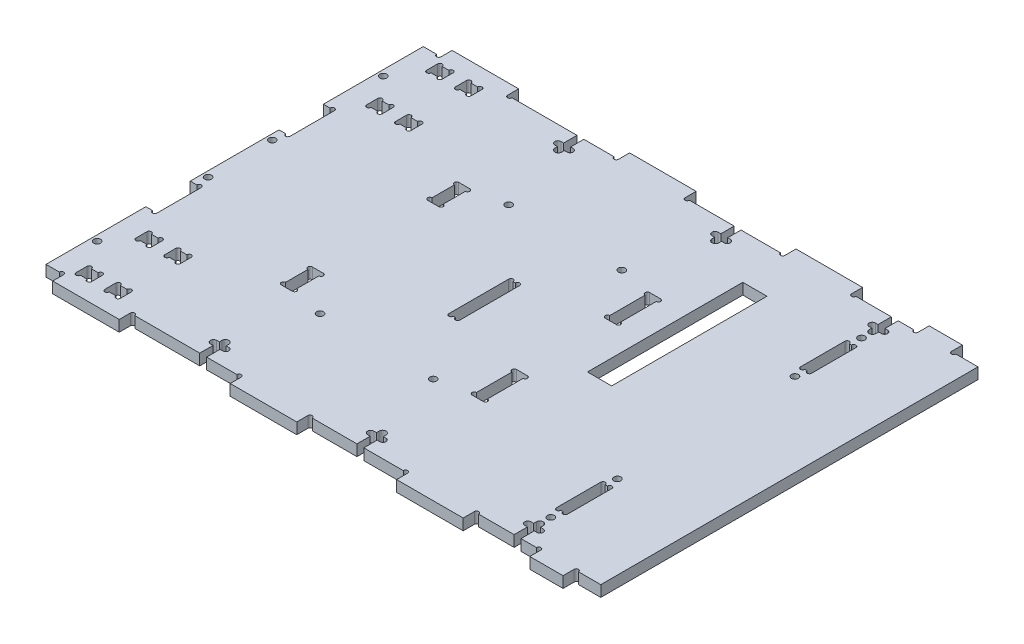
SolidWorks part; units mm, degrees
ref_plane "정면" through (0, 0, 0) normal (0, 0, 1) x (1, 0, 0)
ref_plane "윗면" through (0, 0, 0) normal (0, 1, 0) x (1, 0, 0)
ref_plane "우측면" through (0, 0, 0) normal (1, 0, 0) x (0, 0, -1)
sketch "스케치1" plane through (0, 0, 0) normal (0, 1, 0) x (1, 0, 0)
  line L1 (0, 0) -> (250, 0)
  line L2 (0, 0) -> (0, 170)
  line L3 (0, 170) -> (250, 170)
  line L4 (250, 0) -> (250, 170)
  dimension "D1" = 170
  dimension "D2" = 250
extrude "보스-돌출1" add sketch "스케치1" along normal blind 5
sketch "스케치2" plane through (0, 0, 0) normal (0, -1, 0) x (1, 0, 0)
  line L0 (110, -71.5) -> (110, 0) construction
  line L1 (110, -71.5) -> (115, -71.5)
  line L2 (110, -71.5) -> (110, -98.5)
  line L3 (110, -98.5) -> (115, -98.5)
  line L4 (115, -71.5) -> (115, -98.5)
  line L5 (0, 0) -> (250, 0) construction
  line L6 (110, -98.5) -> (110, -170) construction
  line L7 (250, -170) -> (0, -170) construction
  line L10 (250, 0) -> (250, -170) construction
  line L11 (210, 0) -> (210, -20) construction
  line L12 (210, -20) -> (215, -20)
  line L13 (210, -20) -> (210, -40)
  line L14 (210, -40) -> (215, -40)
  line L15 (215, -20) -> (215, -40)
  line L16 (210, -130) -> (215, -130)
  line L17 (210, -130) -> (210, -150)
  line L18 (210, -150) -> (215, -150)
  line L19 (215, -130) -> (215, -150)
  line L20 (210, -40) -> (210, -130) construction
  line L21 (210, -150) -> (210, -170) construction
  line L22 (215, -130) -> (215, -40) construction
  dimension "D1" = 27
  dimension "D2" = 140
  dimension "D3" = 5
  dimension "D4" = 20
  dimension "D5" = 20
  dimension "D6" = 40
  dimension "D7" = 5
extrude "컷-돌출1" cut sketch "스케치2" against normal blind 10
sketch "스케치3" plane through (0, 5, 0) normal (0, 1, 0) x (1, 0, 0)
  line L0 (133.55, 42.5) -> (130.45, 42.5) construction
  line L1 (133.55, 40) -> (133.55, 45) construction
  line L2 (130.45, 40) -> (130.45, 45) construction
  line L3 (130.45, 42.5) -> (82.55, 42.5) construction
  line L4 (82.55, 40) -> (82.55, 45) construction
  line L5 (82.55, 42.5) -> (79.45, 42.5) construction
  line L6 (79.45, 40) -> (79.45, 45) construction
  line L7 (133.55, 127.5) -> (130.45, 127.5) construction
  line L8 (133.55, 125) -> (133.55, 130) construction
  line L9 (130.45, 125) -> (130.45, 130) construction
  line L10 (130.45, 127.5) -> (82.55, 127.5) construction
  line L11 (82.55, 125) -> (82.55, 130) construction
  line L12 (82.55, 127.5) -> (79.45, 127.5) construction
  line L13 (79.45, 125) -> (79.45, 130) construction
  line L14 (212.5, 46.55) -> (212.5, 43.45) construction
  line L15 (2.5, 101) -> (2.5, 97.9) construction
  line L16 (215, 46.55) -> (210, 46.55) construction
  line L17 (5, 101) -> (0, 101) construction
  line L18 (212.5, 16.55) -> (212.5, 13.45) construction
  line L19 (215, 16.55) -> (210, 16.55) construction
  line L20 (215, 13.45) -> (210, 13.45) construction
  line L21 (215, 43.45) -> (210, 43.45) construction
  line L22 (212.5, 126.55) -> (212.5, 123.45) construction
  line L23 (215, 126.55) -> (210, 126.55) construction
  line L24 (215, 123.45) -> (210, 123.45) construction
  line L25 (212.5, 156.55) -> (212.5, 153.45) construction
  line L26 (215, 156.55) -> (210, 156.55) construction
  line L27 (215, 153.45) -> (210, 153.45) construction
  line L28 (5, 97.9) -> (0, 97.9) construction
  line L31 (2.5, 151) -> (2.5, 147.9) construction
  line L34 (2.5, 22.1) -> (2.5, 19) construction
  line L35 (5, 22.1) -> (0, 22.1) construction
  line L36 (5, 19) -> (0, 19) construction
  line L37 (2.5, 72.1) -> (2.5, 69) construction
  line L38 (5, 72.1) -> (0, 72.1) construction
  line L39 (5, 69) -> (0, 69) construction
  line L40 (5, 151) -> (0, 151) construction
  line L41 (5, 147.9) -> (0, 147.9) construction
  circle A0 centre (81, 127.5) radius 1.55
  circle A1 centre (132, 127.5) radius 1.55
  circle A2 centre (132, 42.5) radius 1.55
  circle A3 centre (81, 42.5) radius 1.55
  circle A4 centre (2.5, 70.55) radius 1.55
  circle A5 centre (2.5, 20.55) radius 1.55
  circle A6 centre (2.5, 99.45) radius 1.55
  circle A7 centre (2.5, 149.45) radius 1.55
  circle A8 centre (212.5, 155) radius 1.55
  circle A9 centre (212.5, 125) radius 1.55
  circle A10 centre (212.5, 15) radius 1.55
  circle A11 centre (212.5, 45) radius 1.55
  dimension "D1" = 3.1
extrude "컷-돌출2" cut sketch "스케치3" against normal blind 10
sketch "스케치4" plane through (0, 0, 0) normal (0, -1, 0) x (1, 0, 0)
  line L1 (0, -125) -> (5, -125)
  line L2 (0, -125) -> (0, -105)
  line L3 (0, -105) -> (5, -105)
  line L4 (5, -125) -> (5, -105)
  line L5 (0, -65) -> (5, -65)
  line L6 (0, -65) -> (0, -45)
  line L7 (0, -45) -> (5, -45)
  line L8 (5, -65) -> (5, -45)
extrude "컷-돌출3" cut sketch "스케치4" against normal blind 5
sketch "스케치5" plane through (0, 0, 0) normal (0, -1, 0) x (1, 0, 0)
  line L2 (5, -45) -> (0, -45) construction
  line L3 (0, -65) -> (5, -65) construction
  line L4 (5, -105) -> (0, -105) construction
  line L5 (0, -125) -> (5, -125) construction
  line L6 (110, -98.5) -> (115, -98.5) construction
  line L7 (115, -71.5) -> (110, -71.5) construction
  line L8 (215, -20) -> (210, -20) construction
  line L9 (210, -40) -> (215, -40) construction
  line L10 (215, -130) -> (210, -130) construction
  line L11 (210, -150) -> (215, -150) construction
  circle A1 centre (4, -45) radius 1
  circle A2 centre (4, -65) radius 1
  circle A5 centre (4, -105) radius 1
  circle A6 centre (4, -125) radius 1
  circle A8 centre (114, -98.5) radius 1
  circle A9 centre (111, -98.5) radius 1
  circle A10 centre (114, -71.5) radius 1
  circle A11 centre (111, -71.5) radius 1
  circle A12 centre (214, -20) radius 1
  circle A13 centre (211, -20) radius 1
  circle A14 centre (214, -40) radius 1
  circle A15 centre (211, -40) radius 1
  circle A16 centre (214, -130) radius 1
  circle A17 centre (211, -130) radius 1
  circle A18 centre (214, -150) radius 1
  circle A19 centre (211, -150) radius 1
  dimension "D1" = 2
extrude "컷-돌출4" cut sketch "스케치5" against normal blind 10
sketch "스케치7" plane through (0, 0, 0) normal (0, -1, 0) x (1, 0, 0)
  line L0 (70.8333, -157.529) -> (0, -157.529) construction
  line L1 (215.25, -8.8) -> (214.05, -8.8)
  line L2 (214.05, 0) -> (214.05, -6)
  line L3 (214.05, -6) -> (210.95, -6) construction
  line L4 (215.25, -6) -> (215.25, -8.8) construction
  line L5 (209.75, -8.8) -> (209.75, -6) construction
  line L6 (212.5, -10) -> (212.5, -12.471) construction
  line L7 (214.05, -10) -> (210.95, -10) construction
  line L8 (209.75, -6) -> (210.95, -6)
  line L9 (210.95, -6) -> (210.95, -8.8) construction
  line L10 (210.95, 0) -> (210.95, -6)
  line L11 (210.95, -8.8) -> (209.75, -8.8)
  line L12 (214.05, -8.8) -> (214.05, -6) construction
  line L13 (210.95, -8.8) -> (210.95, -10)
  line L14 (214.05, -8.8) -> (210.95, -8.8) construction
  line L15 (214.05, -8.8) -> (214.05, -10)
  line L16 (214.05, -6) -> (215.25, -6)
  line L17 (214.05, 0) -> (210.95, 0)
  line L18 (0, -45) -> (0, 0) construction
  line L19 (141.6667, -157.529) -> (70.8333, -157.529) construction
  line L20 (141.6667, -157.529) -> (212.5, -157.529) construction
  line L21 (212.5, -150) -> (212.5, -153.45) construction
  line L22 (143.2167, -161.2) -> (140.1167, -161.2) construction
  line L23 (143.2167, -161.2) -> (143.2167, -164) construction
  line L24 (140.1167, -164) -> (140.1167, -161.2) construction
  line L25 (143.2167, -160) -> (140.1167, -160) construction
  line L26 (141.6667, -160) -> (141.6667, -157.529) construction
  line L27 (138.9167, -161.2) -> (138.9167, -164) construction
  line L28 (144.4167, -164) -> (144.4167, -161.2) construction
  line L29 (143.2167, -164) -> (140.1167, -164) construction
  line L30 (72.3833, -161.2) -> (69.2833, -161.2) construction
  line L31 (72.3833, -161.2) -> (72.3833, -164) construction
  line L32 (69.2833, -164) -> (69.2833, -161.2) construction
  line L33 (72.3833, -160) -> (69.2833, -160) construction
  line L34 (70.8333, -160) -> (70.8333, -157.529) construction
  line L35 (73.5833, -8.8) -> (72.3833, -8.8)
  line L36 (72.3833, 0) -> (72.3833, -6)
  line L37 (72.3833, -6) -> (69.2833, -6) construction
  line L38 (73.5833, -6) -> (73.5833, -8.8) construction
  line L39 (68.0833, -8.8) -> (68.0833, -6) construction
  line L40 (70.8333, -10) -> (70.8333, -12.471) construction
  line L41 (72.3833, -10) -> (69.2833, -10) construction
  line L42 (68.0833, -6) -> (69.2833, -6)
  line L43 (69.2833, -6) -> (69.2833, -8.8) construction
  line L44 (69.2833, 0) -> (69.2833, -6)
  line L45 (69.2833, -8.8) -> (68.0833, -8.8)
  line L46 (72.3833, -8.8) -> (72.3833, -6) construction
  line L47 (69.2833, -8.8) -> (69.2833, -10)
  line L48 (72.3833, -8.8) -> (69.2833, -8.8) construction
  line L49 (72.3833, -8.8) -> (72.3833, -10)
  line L50 (72.3833, -6) -> (73.5833, -6)
  line L51 (72.3833, 0) -> (69.2833, 0)
  line L52 (144.4167, -8.8) -> (143.2167, -8.8)
  line L53 (143.2167, 0) -> (143.2167, -6)
  line L54 (143.2167, -6) -> (140.1167, -6) construction
  line L55 (144.4167, -6) -> (144.4167, -8.8) construction
  line L56 (138.9167, -8.8) -> (138.9167, -6) construction
  line L57 (141.6667, -10) -> (141.6667, -12.471) construction
  line L58 (143.2167, -10) -> (140.1167, -10) construction
  line L59 (138.9167, -6) -> (140.1167, -6)
  line L60 (140.1167, -6) -> (140.1167, -8.8) construction
  line L61 (140.1167, 0) -> (140.1167, -6)
  line L62 (140.1167, -8.8) -> (138.9167, -8.8)
  line L63 (143.2167, -8.8) -> (143.2167, -6) construction
  line L64 (140.1167, -8.8) -> (140.1167, -10)
  line L65 (143.2167, -8.8) -> (140.1167, -8.8) construction
  line L66 (143.2167, -8.8) -> (143.2167, -10)
  line L67 (143.2167, -6) -> (144.4167, -6)
  line L68 (143.2167, 0) -> (140.1167, 0)
  line L69 (68.0833, -161.2) -> (68.0833, -164) construction
  line L70 (212.5, -20) -> (212.5, -16.55) construction
  line L71 (213, -20) -> (212, -20) construction
  line L72 (141.6667, -12.471) -> (212.5, -12.471) construction
  line L73 (141.6667, -12.471) -> (70.8333, -12.471) construction
  line L74 (70.8333, -12.471) -> (0, -12.471) construction
  line L75 (0, -85) -> (250, -85) construction
  line L76 (0, -105) -> (0, -65) construction
  line L77 (250, 0) -> (250, -170) construction
  line L78 (73.5833, -164) -> (73.5833, -161.2) construction
  line L79 (72.3833, -164) -> (69.2833, -164) construction
  line L80 (214.05, -161.2) -> (210.95, -161.2) construction
  line L81 (214.05, -161.2) -> (214.05, -164) construction
  line L82 (210.95, -164) -> (210.95, -161.2) construction
  line L83 (214.05, -160) -> (210.95, -160) construction
  line L84 (212.5, -160) -> (212.5, -157.529) construction
  line L85 (209.75, -161.2) -> (209.75, -164) construction
  line L86 (215.25, -164) -> (215.25, -161.2) construction
  line L87 (214.05, -164) -> (210.95, -164) construction
  line L88 (143.2167, -170) -> (140.1167, -170)
  line L89 (143.2167, -164) -> (144.4167, -164)
  line L90 (143.2167, -161.2) -> (143.2167, -160)
  line L91 (140.1167, -161.2) -> (140.1167, -160)
  line L92 (140.1167, -161.2) -> (138.9167, -161.2)
  line L93 (140.1167, -170) -> (140.1167, -164)
  line L94 (138.9167, -164) -> (140.1167, -164)
  line L95 (143.2167, -170) -> (143.2167, -164)
  line L96 (144.4167, -161.2) -> (143.2167, -161.2)
  line L97 (72.3833, -170) -> (69.2833, -170)
  line L98 (72.3833, -164) -> (73.5833, -164)
  line L99 (72.3833, -161.2) -> (72.3833, -160)
  line L100 (69.2833, -161.2) -> (69.2833, -160)
  line L101 (69.2833, -161.2) -> (68.0833, -161.2)
  line L102 (69.2833, -170) -> (69.2833, -164)
  line L103 (68.0833, -164) -> (69.2833, -164)
  line L104 (72.3833, -170) -> (72.3833, -164)
  line L105 (73.5833, -161.2) -> (72.3833, -161.2)
  line L106 (214.05, -170) -> (210.95, -170)
  line L107 (214.05, -164) -> (215.25, -164)
  line L108 (214.05, -161.2) -> (214.05, -160)
  line L109 (210.95, -161.2) -> (210.95, -160)
  line L110 (210.95, -161.2) -> (209.75, -161.2)
  line L111 (210.95, -170) -> (210.95, -164)
  line L112 (209.75, -164) -> (210.95, -164)
  line L113 (214.05, -170) -> (214.05, -164)
  line L114 (215.25, -161.2) -> (214.05, -161.2)
  arc A0 (209.75, -6) -> (209.75, -8.8) centre (209.75, -7.4) ccw
  arc A1 (215.25, -8.8) -> (215.25, -6) centre (215.25, -7.4) ccw
  arc A2 (210.95, -10) -> (214.05, -10) centre (212.5, -10) ccw
  arc A3 (140.1167, -160) -> (143.2167, -160) centre (141.6667, -160) cw
  arc A4 (144.4167, -161.2) -> (144.4167, -164) centre (144.4167, -162.6) cw
  arc A5 (138.9167, -164) -> (138.9167, -161.2) centre (138.9167, -162.6) cw
  arc A6 (68.0833, -6) -> (68.0833, -8.8) centre (68.0833, -7.4) ccw
  arc A7 (73.5833, -8.8) -> (73.5833, -6) centre (73.5833, -7.4) ccw
  arc A8 (69.2833, -10) -> (72.3833, -10) centre (70.8333, -10) ccw
  arc A9 (138.9167, -6) -> (138.9167, -8.8) centre (138.9167, -7.4) ccw
  arc A10 (144.4167, -8.8) -> (144.4167, -6) centre (144.4167, -7.4) ccw
  arc A11 (140.1167, -10) -> (143.2167, -10) centre (141.6667, -10) ccw
  circle A12 centre (212.5, -15) radius 1.55 construction
  arc A13 (69.2833, -160) -> (72.3833, -160) centre (70.8333, -160) cw
  arc A14 (73.5833, -161.2) -> (73.5833, -164) centre (73.5833, -162.6) cw
  arc A15 (68.0833, -164) -> (68.0833, -161.2) centre (68.0833, -162.6) cw
  arc A16 (210.95, -160) -> (214.05, -160) centre (212.5, -160) cw
  arc A17 (215.25, -161.2) -> (215.25, -164) centre (215.25, -162.6) cw
  arc A18 (209.75, -164) -> (209.75, -161.2) centre (209.75, -162.6) cw
  dimension "D2" = 3.1
  dimension "D3" = 5.5
  dimension "D4" = 2.8
  dimension "D8" = 3.1
  dimension "D9" = 5.5
  dimension "D10" = 2.8
  dimension "D11" = 3.1
  dimension "D12" = 5.5
  dimension "D13" = 2.8
extrude "컷-돌출5" cut sketch "스케치7" against normal blind 10
sketch "스케치8" plane through (0, 0, 0) normal (0, -1, 0) x (1, 0, 0)
  line L0 (0, 0) -> (69.2833, 0) construction
  line L1 (8, 0) -> (38, 0)
  line L2 (8, 0) -> (8, 5)
  line L3 (8, 5) -> (38, 5)
  line L4 (38, 0) -> (38, 5)
  line L5 (0, 5) -> (8, 5) construction
  line L6 (72.3833, 0) -> (140.1167, 0) construction
  line L7 (88, 5) -> (118, 5)
  line L8 (88, 5) -> (88, 0)
  line L9 (88, 0) -> (118, 0)
  line L10 (118, 5) -> (118, 0)
  line L11 (143.2167, 0) -> (210.95, 0) construction
  line L12 (163, 5) -> (193, 5)
  line L13 (163, 5) -> (163, 0)
  line L14 (163, 0) -> (193, 0)
  line L15 (193, 5) -> (193, 0)
  line L16 (214.05, 0) -> (250, 0) construction
  line L17 (223, 5) -> (238, 5)
  line L18 (223, 5) -> (223, 0)
  line L19 (223, 0) -> (238, 0)
  line L20 (238, 5) -> (238, 0)
  line L21 (250, 0) -> (250, -170) construction
  line L22 (0, -85) -> (250, -85) construction
  line L23 (0, -105) -> (0, -65) construction
  line L24 (238, -175) -> (238, -170)
  line L25 (223, -170) -> (238, -170)
  line L26 (223, -175) -> (223, -170)
  line L27 (223, -175) -> (238, -175)
  line L28 (193, -175) -> (193, -170)
  line L29 (163, -170) -> (193, -170)
  line L30 (163, -175) -> (163, -170)
  line L31 (163, -175) -> (193, -175)
  line L32 (118, -175) -> (118, -170)
  line L33 (88, -170) -> (118, -170)
  line L34 (88, -175) -> (88, -170)
  line L35 (88, -175) -> (118, -175)
  line L36 (38, -170) -> (38, -175)
  line L37 (8, -175) -> (38, -175)
  line L38 (8, -170) -> (8, -175)
  line L39 (8, -170) -> (38, -170)
  dimension "D1" = 12
  dimension "D2" = 15
  dimension "D3" = 30
  dimension "D4" = 30
  dimension "D5" = 45
  dimension "D6" = 30
  dimension "D7" = 50
  dimension "D8" = 30
extrude "보스-돌출2" add sketch "스케치8" against normal blind 5
sketch "스케치9" plane through (0, 0, 0) normal (0, -1, 0) x (1, 0, 0)
  line L0 (0, 0) -> (8, 0) construction
  line L1 (38, 0) -> (69.2833, 0) construction
  line L2 (72.3833, 0) -> (88, 0) construction
  line L3 (118, 0) -> (140.1167, 0) construction
  line L4 (143.2167, 0) -> (163, 0) construction
  line L5 (214.05, 0) -> (223, 0) construction
  line L6 (193, 0) -> (210.95, 0) construction
  line L7 (238, 0) -> (250, 0) construction
  line L8 (0, -85) -> (250, -85) construction
  line L9 (0, -105) -> (0, -65) construction
  line L10 (250, 0) -> (250, -170) construction
  circle A0 centre (7, 0) radius 1
  circle A1 centre (39, 0) radius 1
  circle A2 centre (87, 0) radius 1
  circle A3 centre (119, 0) radius 1
  circle A4 centre (162, 0) radius 1
  circle A5 centre (222, 0) radius 1
  circle A6 centre (194, 0) radius 1
  circle A7 centre (239, 0) radius 1
  circle A8 centre (239, -170) radius 1
  circle A9 centre (194, -170) radius 1
  circle A10 centre (222, -170) radius 1
  circle A11 centre (162, -170) radius 1
  circle A12 centre (119, -170) radius 1
  circle A13 centre (87, -170) radius 1
  circle A14 centre (39, -170) radius 1
  circle A15 centre (7, -170) radius 1
  dimension "D1" = 2
extrude "컷-돌출6" cut sketch "스케치9" against normal blind 5
sketch "스케치13" plane through (0, 5, 0) normal (0, 1, 0) x (1, 0, 0)
  line L0 (30, 8.5) -> (30, 30.5) construction
  line L1 (30, 8.5) -> (23, 8.5)
  line L2 (30, 8.5) -> (30, 3.5)
  line L3 (30, 3.5) -> (23, 3.5)
  line L4 (23, 8.5) -> (23, 3.5)
  line L5 (17, 8.5) -> (10, 8.5)
  line L6 (17, 8.5) -> (17, 3.5)
  line L7 (17, 3.5) -> (10, 3.5)
  line L8 (10, 8.5) -> (10, 3.5)
  line L9 (30, 19.5) -> (11.9274, 19.5) construction
  line L10 (10, 30.5) -> (10, 35.5)
  line L11 (17, 35.5) -> (10, 35.5)
  line L12 (17, 30.5) -> (17, 35.5)
  line L13 (17, 30.5) -> (10, 30.5)
  line L14 (23, 30.5) -> (23, 35.5)
  line L15 (30, 35.5) -> (23, 35.5)
  line L16 (30, 30.5) -> (30, 35.5)
  line L17 (30, 30.5) -> (23, 30.5)
  line L18 (0, 85) -> (49.672, 85) construction
  line L19 (0, 105) -> (0, 65) construction
  line L20 (30, 150.5) -> (11.9274, 150.5) construction
  line L21 (30, 161.5) -> (30, 139.5) construction
  line L22 (30, 139.5) -> (23, 139.5)
  line L23 (30, 139.5) -> (30, 134.5)
  line L24 (30, 134.5) -> (23, 134.5)
  line L25 (23, 139.5) -> (23, 134.5)
  line L26 (17, 139.5) -> (10, 139.5)
  line L27 (17, 139.5) -> (17, 134.5)
  line L28 (17, 134.5) -> (10, 134.5)
  line L29 (10, 139.5) -> (10, 134.5)
  line L30 (10, 161.5) -> (10, 166.5)
  line L31 (17, 166.5) -> (10, 166.5)
  line L32 (17, 161.5) -> (17, 166.5)
  line L33 (17, 161.5) -> (10, 161.5)
  line L34 (23, 161.5) -> (23, 166.5)
  line L35 (30, 166.5) -> (23, 166.5)
  line L36 (30, 161.5) -> (30, 166.5)
  line L37 (30, 161.5) -> (23, 161.5)
extrude "컷-돌출9" cut sketch "스케치13" against normal blind 10
sketch "스케치14" plane through (0, 0, 0) normal (0, -1, 0) x (1, 0, 0)
  line L0 (10, -8.5) -> (17, -8.5) construction
  line L1 (17, -3.5) -> (10, -3.5) construction
  line L2 (17, -30.5) -> (23, -30.5) construction
  line L3 (23, -30.5) -> (23, -8.5) construction
  line L4 (23, -8.5) -> (17, -8.5) construction
  line L5 (17, -8.5) -> (17, -30.5) construction
  line L6 (20, -30.5) -> (20, -8.5) construction
  line L7 (17, -19.5) -> (23, -19.5) construction
  line L8 (0, -85) -> (55.1733, -85) construction
  line L9 (0, -105) -> (0, -65) construction
  line L10 (17, -150.5) -> (23, -150.5) construction
  line L11 (20, -139.5) -> (20, -161.5) construction
  line L12 (17, -161.5) -> (17, -139.5) construction
  line L13 (23, -161.5) -> (17, -161.5) construction
  line L14 (23, -139.5) -> (23, -161.5) construction
  line L15 (17, -139.5) -> (23, -139.5) construction
  circle A0 centre (11, -8.5) radius 1
  circle A1 centre (11, -3.5) radius 1
  circle A2 centre (16, -3.5) radius 1
  circle A3 centre (16, -8.5) radius 1
  circle A4 centre (24, -8.5) radius 1
  circle A5 centre (24, -3.5) radius 1
  circle A6 centre (29, -3.5) radius 1
  circle A7 centre (29, -8.5) radius 1
  circle A8 centre (29, -30.5) radius 1
  circle A9 centre (29, -35.5) radius 1
  circle A10 centre (24, -35.5) radius 1
  circle A11 centre (24, -30.5) radius 1
  circle A12 centre (16, -30.5) radius 1
  circle A13 centre (16, -35.5) radius 1
  circle A14 centre (11, -35.5) radius 1
  circle A15 centre (11, -30.5) radius 1
  circle A16 centre (11, -139.5) radius 1
  circle A17 centre (11, -134.5) radius 1
  circle A18 centre (16, -134.5) radius 1
  circle A19 centre (16, -139.5) radius 1
  circle A20 centre (24, -139.5) radius 1
  circle A21 centre (24, -134.5) radius 1
  circle A22 centre (29, -134.5) radius 1
  circle A23 centre (29, -139.5) radius 1
  circle A24 centre (29, -161.5) radius 1
  circle A25 centre (29, -166.5) radius 1
  circle A26 centre (24, -166.5) radius 1
  circle A27 centre (24, -161.5) radius 1
  circle A28 centre (16, -161.5) radius 1
  circle A29 centre (16, -166.5) radius 1
  circle A30 centre (11, -166.5) radius 1
  circle A31 centre (11, -161.5) radius 1
  dimension "D1" = 2
extrude "컷-돌출10" cut sketch "스케치14" against normal blind 10
sketch "스케치15" plane through (0, 5, 0) normal (0, 1, 0) x (1, 0, 0)
  line L1 (61, 125) -> (66, 125)
  line L2 (61, 125) -> (61, 111)
  line L3 (61, 111) -> (66, 111)
  line L4 (66, 125) -> (66, 111)
  line L5 (61, 45) -> (66, 45)
  line L6 (61, 45) -> (61, 59)
  line L7 (61, 59) -> (66, 59)
  line L8 (66, 45) -> (66, 59)
  line L9 (147, 65) -> (152, 65)
  line L10 (147, 65) -> (147, 45)
  line L11 (147, 45) -> (152, 45)
  line L12 (152, 65) -> (152, 45)
  line L13 (147, 105) -> (152, 105)
  line L14 (147, 105) -> (147, 125)
  line L15 (147, 125) -> (152, 125)
  line L16 (152, 105) -> (152, 125)
  arc A0 (66, 56.5) -> (66, 59) centre (66, 57.75) ccw construction
  dimension "D1" = 5
extrude "컷-돌출11" cut sketch "스케치15" against normal blind 10
sketch "스케치16" plane through (0, 5, 0) normal (0, 1, 0) x (1, 0, 0)
  line L0 (61, 59) -> (61, 45) construction
  line L1 (66, 45) -> (66, 59) construction
  line L2 (61, 125) -> (61, 111) construction
  line L3 (66, 111) -> (66, 125) construction
  line L4 (152, 105) -> (152, 125) construction
  line L5 (147, 125) -> (147, 105) construction
  line L6 (147, 65) -> (147, 45) construction
  line L7 (152, 45) -> (152, 65) construction
  circle A0 centre (61, 46) radius 1
  circle A1 centre (66, 46) radius 1
  circle A2 centre (66, 58) radius 1
  circle A3 centre (61, 58) radius 1
  circle A4 centre (61, 112) radius 1
  circle A5 centre (66, 112) radius 1
  circle A6 centre (66, 124) radius 1
  circle A7 centre (61, 124) radius 1
  circle A8 centre (152, 124) radius 1
  circle A10 centre (147, 124) radius 1
  circle A11 centre (147, 64) radius 1
  circle A12 centre (152, 64) radius 1
  circle A13 centre (152, 106) radius 1
  circle A14 centre (147, 106) radius 1
  circle A15 centre (147, 46) radius 1
  circle A16 centre (152, 46) radius 1
  dimension "D1" = 2
extrude "컷-돌출12" cut sketch "스케치16" against normal blind 10
sketch "스케치17" plane through (0, 5, 0) normal (0, 1, 0) x (1, 0, 0)
  line L0 (169, 97.5569) -> (169, 95.1974) construction
  line L1 (164, 80) -> (174.9, 80)
  line L2 (164, 80) -> (164, 150)
  line L3 (164, 150) -> (174.9, 150)
  line L4 (174.9, 80) -> (174.9, 150)
  line L6 (169.9, 97.5569) -> (169.9, 95.1974) construction
  line L7 (-5, 0) -> (295, 0) construction
  line L8 (161, 170) -> (143.2167, 170) construction
  dimension "D1" = 5
  dimension "D2" = 5
  dimension "D3" = 80
  dimension "D4" = 20
extrude "컷-돌출13" cut sketch "스케치17" against normal blind 10
